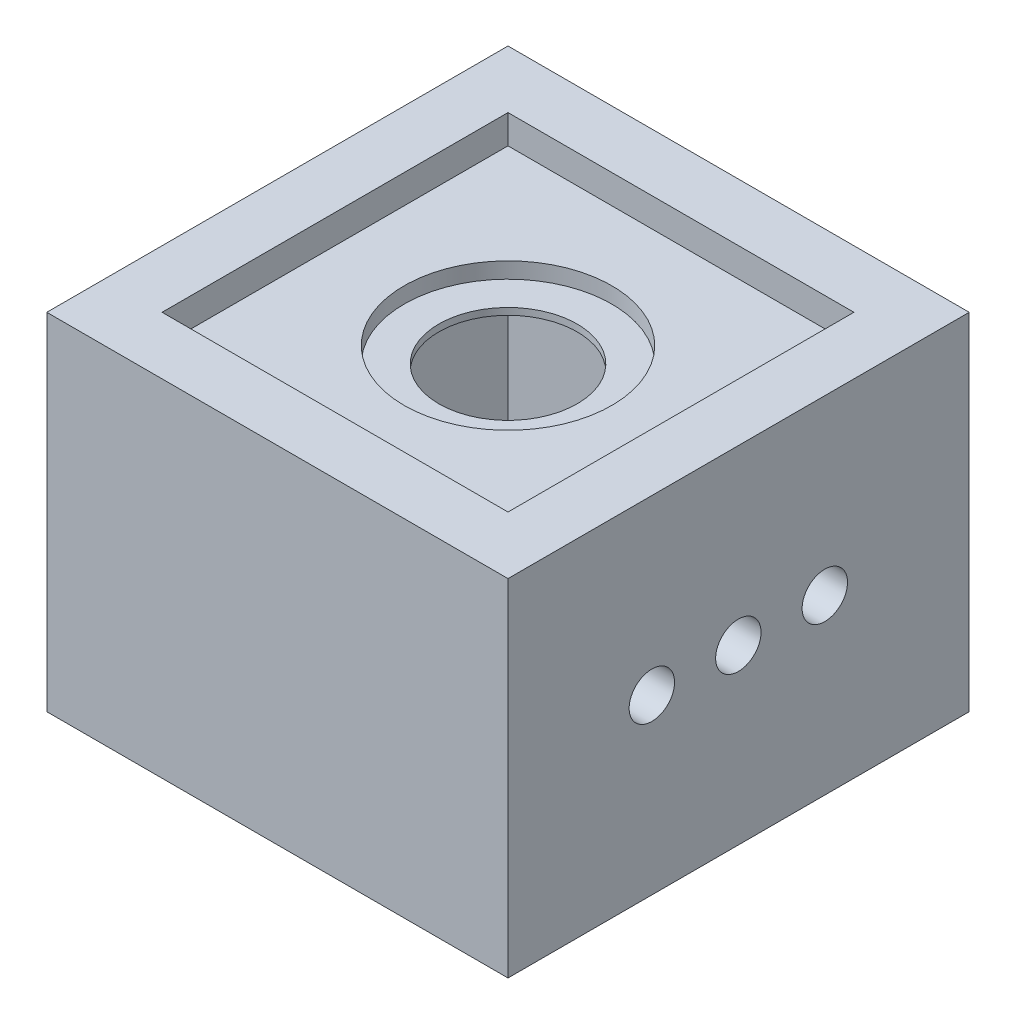
SolidWorks part; units mm, degrees
ref_plane "Front Plane" through (0, 0, 0) normal (0, 0, 1) x (1, 0, 0)
ref_plane "Top Plane" through (0, 0, 0) normal (0, 1, 0) x (1, 0, 0)
ref_plane "Right Plane" through (0, 0, 0) normal (1, 0, 0) x (0, 0, -1)
sketch "Sketch1" plane through (0, 0, 0) normal (0, 1, 0) x (1, 0, 0)
  line L1 (-38.1, -38.1) -> (38.1, -38.1)
  line L2 (-38.1, -38.1) -> (-38.1, 38.1)
  line L3 (-38.1, 38.1) -> (38.1, 38.1)
  line L4 (38.1, -38.1) -> (38.1, 38.1)
  line L5 (-38.1, -38.1) -> (38.1, 38.1) construction
  line L6 (-38.1, 38.1) -> (38.1, -38.1) construction
  line L7 (-50.8, -50.8) -> (50.8, -50.8)
  line L8 (-50.8, -50.8) -> (-50.8, 50.8)
  line L9 (-50.8, 50.8) -> (50.8, 50.8)
  line L10 (50.8, -50.8) -> (50.8, 50.8)
  line L11 (-50.8, -50.8) -> (50.8, 50.8) construction
  line L12 (-50.8, 50.8) -> (50.8, -50.8) construction
  point P0 (0, 0)
  point P6 (0, 0)
  dimension "D1" = 76.2
  dimension "D2" = 76.2
  dimension "D3" = 101.6
  dimension "D4" = 101.6
extrude "Boss-Extrude1" add sketch "Sketch1" along normal blind 76.2
sketch "Sketch2" plane through (0, 76.2, 0) normal (0, 1, 0) x (1, 0, 0)
  line L1 (-38.1, -38.1) -> (38.1, -38.1)
  line L2 (-38.1, -38.1) -> (-38.1, 38.1)
  line L3 (-38.1, 38.1) -> (38.1, 38.1)
  line L4 (38.1, -38.1) -> (38.1, 38.1)
  line L5 (-38.1, -38.1) -> (38.1, 38.1) construction
  line L6 (-38.1, 38.1) -> (38.1, -38.1) construction
  circle A0 centre (0, 0) radius 15.24
  point P0 (0, 0)
  dimension "D1" = 30.48
extrude "Boss-Extrude2" add sketch "Sketch2" against normal blind 5 from offset 6.35 offset against normal yes
sketch "Sketch3" plane through (0, 69.85, 0) normal (0, 1, 0) x (1, 0, 0)
  circle A0 centre (0, 0) radius 22.86
  dimension "D1" = 45.72
extrude "Cut-Extrude2" cut sketch "Sketch3" against normal blind 3.5
sketch "Sketch4" plane through (50.8, 0, 0) normal (1, 0, 0) x (0, 0, -1)
  line L0 (-50.8, 76.2) -> (50.8, 76.2) construction
  line L1 (50.8, 76.2) -> (50.8, 0) construction
  line L2 (-50.8, 76.2) -> (50.8, 76.2) construction
  line L3 (50.8, 0) -> (50.8, 76.2) construction
  line L4 (-19.1107, 38.1) -> (18.9893, 38.1)
  circle A0 centre (-19.1107, 38.1) radius 5
  circle A1 centre (-0.0607, 38.1) radius 5
  circle A2 centre (18.9893, 38.1) radius 5
  point P8 (-0.0607, 38.1)
  point P12 (-0.0607, 38.1)
extrude "Cut-Extrude3" cut sketch "Sketch4" against normal up to surface (12.7 mm away) up to face at (38.1, 32.425, 0)
